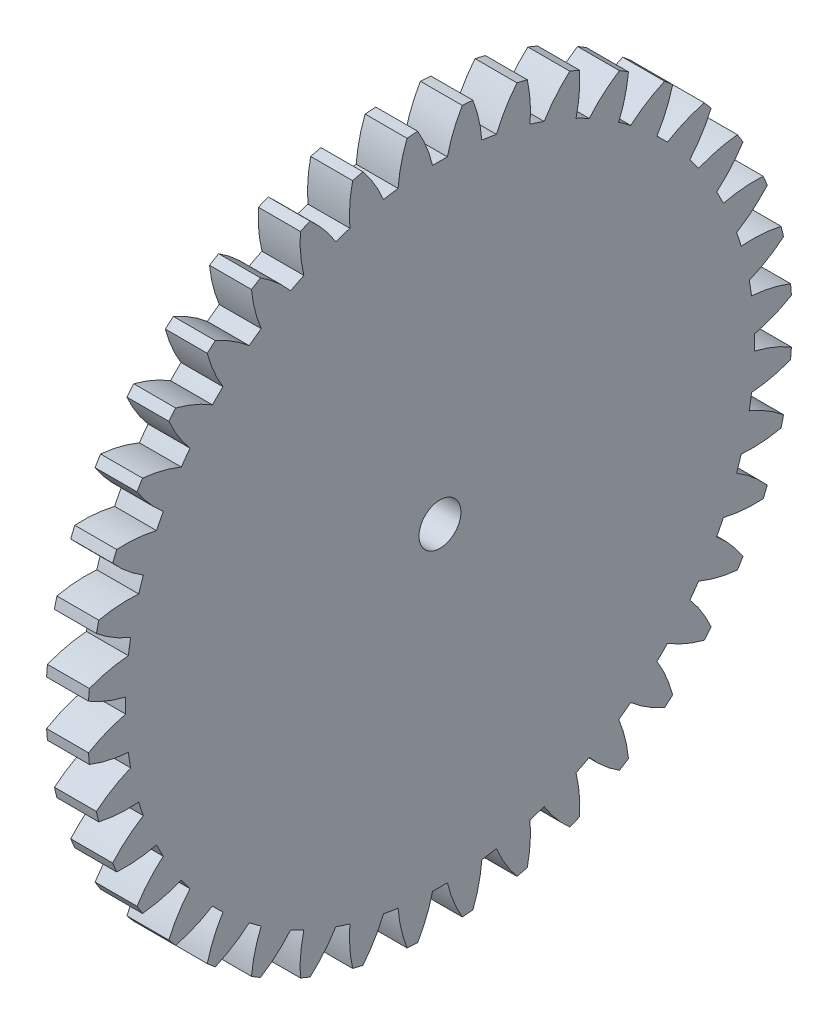
SolidWorks part; units mm, degrees
ref_plane "Plane1" through (0, 0, 0) normal (0, 0, 1) x (1, 0, 0)
ref_plane "Plane2" through (0, 0, 0) normal (0, 1, 0) x (1, 0, 0)
ref_plane "Plane3" through (0, 0, 0) normal (1, 0, 0) x (0, 0, -1)
sketch "HoldingSke" plane through (0, 0, 0) normal (0, 1, 0) x (1, 0, 0)
  line L0 (0, 0) -> (0.383, -0.3214)
  line L1 (-15, 0) -> (100, 0) construction
  line L2 (0, 0) -> (-2.1039, 2.3779)
  line L3 (0, 0) -> (-11.863, 4.5341)
  line L4 (0, 0) -> (6.6156, 5.5511)
  line L5 (0, 0) -> (-46.8476, -17.4728)
  line L6 (0, 0) -> (-4.1448, -2.7965)
  line L7 (-2.1039, 2.3779) -> (8.6586, 51.2059)
  line L8 (-76.2, 54.61) -> (-75.3, 54.61)
  line L9 (-71.009, 38.7566) -> (-53.1078, 45.2721)
  line L10 (-76.2, 71.12) -> (104.1128, 71.12)
  line L11 (0, 0) -> (-5, 0)
  line L12 (-76.2, 101.6) -> (-76.133, 101.6)
  line L13 (24.9733, 27.94) -> (52.9518, 28.4284)
  line L14 (24.9733, 27.94) -> (24.9743, 27.94)
  line L15 (24.9733, 27.94) -> (100.4006, 29.5858)
  line L16 (-63.627, -2) -> (-12.827, -2)
  circle A0 centre (0, 0) radius 2.5
  circle A1 centre (0, 0) radius 37.499
  circle A2 centre (0, 0) radius 37.5
  circle A3 centre (0, 0) radius 2.5
  dimension "MHD" = 74.998
  dimension "Hub_dia" = 75
  dimension "Bore" = 5
  dimension "MBD" = 5
  dimension "Num_teeth" = 40
  dimension "Pitch" = 0.5
  dimension "Overall_len" = 50
  dimension "Show_teeth" = 40
  dimension "Thickness" = 5
  dimension "OAL" = 50.0001
  dimension "T_dim" = 0.9
  dimension "Ap" = 20
  dimension "H" = 19.05
  dimension "Pitch_radius" = 180.3128
  dimension "Width" = 5
  dimension "Backlash" = 0.067
  dimension "Addendum_fac" = 1
  dimension "Dedendum_fac" = 1.25
  dimension "Clearance_fac" = 0.25
  dimension "Dedendum_add" = 0.001
  dimension "Module" = 2
sketch "BasProSke" plane through (0, 0, 0) normal (0, 1, 0) x (1, 0, 0)
  line L0 (-10, 0) -> (60, 0) construction
  line L1 (0, 0) -> (0, 42)
  line L2 (0, 0) -> (5, 0)
  line L3 (5, 0) -> (5, 42)
  line L4 (5, 42) -> (0, 42)
  dimension "Thickness" = 5
  dimension "Diameter" = 84
revolve "Base-Revolve" add sketch "BasProSke" angle 360 about L0
sketch "TooCutSke" plane through (0, 0, 0) normal (1, 0, 0) x (0, 0, -1)
  line L1 (0, 0) -> (0, 107) construction
  line L2 (0, 0) -> (-1.6876, 39.9644) construction
  line L3 (0, 0) -> (-6.2726, 79.7007) construction
  line L4 (-1.6876, 39.9644) -> (-3.1363, 39.8504) construction
  arc A0 (0.8828, 37.4886) -> (-0.8828, 37.4886) centre (0, 0) ccw
  arc A1 (2.6784, 41.94) -> (-2.6784, 41.94) centre (0, 0) ccw
  circle A2 centre (0, 0) radius 40 construction
  circle A3 centre (0, 0) radius 37.5877 construction
  arc A4 (-0.8828, 37.4886) -> (-2.6784, 41.94) centre (-16.451, 33.7965) ccw
  arc A5 (2.6784, 41.94) -> (0.8828, 37.4886) centre (16.451, 33.7965) ccw
  dimension "Root_dia" = 74.998
  dimension "Overcut_dia" = 84.0508
  dimension "Pitch_dia" = 80
  dimension "Base_dia" = 75.1754
  dimension "Flank_rad" = 16
  dimension "Half_ang" = 4.5
  dimension "Half_CT" = 1.4531
extrude "ToothCut" cut sketch "TooCutSke" along normal through all
fillet "Breaks" [suppressed] radius 0.04
fillet "RootFillets" [suppressed] radius 0.501
pattern_circular "TeethCuts" count 40 every 9 about axis through (-10, 0, 0) along (1, 0, 0) of "ToothCut", "RootFillets", "Breaks"
sketch "HubNeaOneSke" plane through (0, 0, 0) normal (-1, 0, 0) x (0, 0, 1)
  circle A0 centre (0, 0) radius 37.499
  dimension "Diameter" = 74.998
extrude "HubNearOne" [suppressed] add sketch "HubNeaOneSke" along normal blind 45.0001
sketch "HubNeaBotSke" plane through (0, 0, 0) normal (-1, 0, 0) x (0, 0, 1)
  circle A0 centre (0, 0) radius 37.499
  dimension "Diameter" = 74.998
extrude "HubNearBoth" [suppressed] add sketch "HubNeaBotSke" along normal blind 22.5
ref_plane "FarPln" through (5, 0, 0) normal (1, 0, 0) x (0, 0, -1)
sketch "HubFarSke" plane through (5, 0, 0) normal (1, 0, 0) x (0, 0, -1)
  circle A0 centre (0, 0) radius 37.499
  dimension "Diameter" = 74.998
extrude "HubFar" [suppressed] add sketch "HubFarSke" along normal blind 22.5
sketch "BorSke" plane through (0, 0, 0) normal (1, 0, 0) x (0, 0, -1)
  circle A0 centre (0, 0) radius 2.5
  dimension "Diameter" = 5
extrude "Bore" cut sketch "BorSke" along normal mid plane 100.0001
sketch "KeySke" plane through (0, 0, 0) normal (1, 0, 0) x (0, 0, -1)
  line L0 (-1, 0) -> (-1, 3.4)
  line L1 (-1, 3.4) -> (1, 3.4)
  line L2 (1, 3.4) -> (1, 0)
  line L3 (0, 0) -> (0, 34) construction
  line L4 (-1, 0) -> (1, 0)
  dimension "Offset" = 3.4
  dimension "Width" = 2
extrude "Keyway" [suppressed] cut sketch "KeySke" along normal mid plane 100.0001
pattern_circular "Keyway2" [suppressed] count 2 every 90 about axis through (-10, 0, 0) along (1, 0, 0)
equation "' \"Module@HoldingSke\" = 6.35"
equation "' \"Num_teeth@HoldingSke\" = 12"
equation "' \"Ap@HoldingSke\" =  20"
equation "' \"Ap@HoldingSke\" = 20"
equation "' \"Width@HoldingSke\" = 0.5 * 25.4"
equation "' \"Hub_dia@HoldingSke\"= 1 * 25.4"
equation "' \"Hub_dia@HoldingSke\" = 1 * 25.4"
equation "' \"Overall_len@HoldingSke\" = 1.0 * 25.4"
equation "' \"Bore@HoldingSke\" = 0.75 * 25.4"
equation "' \"T_dim@HoldingSke\" = 0.1 * 25.4"
equation "' \"Width@KeySke\" = 0.25 * 25.4"
equation "' \"Show_teeth@HoldingSke\" = 13"
equation "' \"Backlash@HoldingSke\" = 0.009 * 25.4"
equation "' \"Addendum_fac@HoldingSke\" = 1.0"
equation "' \"Dedendum_fac@HoldingSke\" = 1.25"
equation "' \"Dedendum_add@HoldingSke\" = 0.00005 * 25.4"
equation "' \"Clearance_fac@HoldingSke\" = 0.25"
equation "\"Pitch@HoldingSke\" = 1 / \"Module@HoldingSke\""
equation "\"Overcut_dia@TooCutSke\" = (\"Num_teeth@HoldingSke\" + 2 * \"Addendum_fac@HoldingSke\") / \"Pitch@HoldingSke\" + 0.002 * 25.4"
equation "\"Pitch_dia@TooCutSke\" = \"Num_teeth@HoldingSke\" / \"Pitch@HoldingSke\""
equation "\"Base_dia@TooCutSke\" = \"Num_teeth@HoldingSke\" / \"Pitch@HoldingSke\" * cos((\"Ap@HoldingSke\"  * 3.14159265 / 180))"
equation "\"Root_dia@TooCutSke\" = (\"Num_teeth@HoldingSke\" + 2) / \"Pitch@HoldingSke\" - 2 * (\"Addendum_fac@HoldingSke\" + \"Dedendum_fac@HoldingSke\") / \"Pitch@HoldingSke\" - \"Dedendum_add@HoldingSke\" * 2"
equation "\"Half_ang@TooCutSke\" = 180 / \"Num_teeth@HoldingSke\""
equation "\"Half_CT@TooCutSke\" = \"Num_teeth@HoldingSke\" / \"Pitch@HoldingSke\" * sin((3.14159265 / 2 / \"Num_teeth@HoldingSke\")) / 2 - 7 * \"Backlash@HoldingSke\" / 4"
equation "\"Flank_rad@TooCutSke\" = \"Num_teeth@HoldingSke\" / \"Pitch@HoldingSke\" / 5"
equation "\"Radius@RootFillets\" = \"Clearance_fac@HoldingSke\" / \"Pitch@HoldingSke\" + \"Dedendum_add@HoldingSke\""
equation "\"Break_rad@Breaks\" = 0.02 / \"Pitch@HoldingSke\""
equation "\"Thickness@HoldingSke\" = \"Width@HoldingSke\""
equation "\"OAL@HoldingSke\" = \"Thickness@HoldingSke\""
equation "\"MHD@HoldingSke\" = (\"Num_teeth@HoldingSke\" + 2) / \"Pitch@HoldingSke\" - 2 * (\"Addendum_fac@HoldingSke\" + \"Dedendum_fac@HoldingSke\")  / \"Pitch@HoldingSke\" - \"Dedendum_add@HoldingSke\" * 2"
equation "\"MBD@HoldingSke\" = (\"Num_teeth@HoldingSke\" + 2) / \"Pitch@HoldingSke\" - 2 * (\"Addendum_fac@HoldingSke\" + \"Dedendum_fac@HoldingSke\")  / \"Pitch@HoldingSke\" - \"Dedendum_add@HoldingSke\" * 2 - 0.002 * 25.4"
equation "\"MHD@HoldingSke\" = ((sgn( \"MHD@HoldingSke\" - \"Hub_dia@HoldingSke\" )-1)*( \"MHD@HoldingSke\" - \"Hub_dia@HoldingSke\" ))/-2+ \"Hub_dia@HoldingSke\""
equation "\"MBD@HoldingSke\" = ((sgn( \"MBD@HoldingSke\" - \"Bore@HoldingSke\" )-1)*( \"MBD@HoldingSke\" - \"Bore@HoldingSke\" ))/-2+ \"Bore@HoldingSke\""
equation "\"OAL@HoldingSke\" = ((sgn( \"OAL@HoldingSke\" - \"Overall_len@HoldingSke\" )+1)*( \"OAL@HoldingSke\" - \"Overall_len@HoldingSke\" ))/2 + \"Overall_len@HoldingSke\" + 0.000002 * 25.4"
equation "\"Num_teeth@TeethCuts\" = int( \"Show_teeth@HoldingSke\" ) + 1"
equation "\"Num_teeth@TeethCuts\" = ((sgn( \"Num_teeth@TeethCuts\" - \"Num_teeth@HoldingSke\" )-1)*( \"Num_teeth@TeethCuts\" - \"Num_teeth@HoldingSke\" ))/-2+ \"Num_teeth@HoldingSke\""
equation "\"Num_teeth@TeethCuts\" = ((sgn( \"Num_teeth@TeethCuts\" - 2.0)+1)*( \"Num_teeth@TeethCuts\" - 2.0))/2 +2.0"
equation "\"Angle@TeethCuts\" = 360.0 / \"Num_teeth@HoldingSke\""
equation "\"Diameter@BasProSke\" = (\"Num_teeth@HoldingSke\" + 2 * \"Addendum_fac@HoldingSke\") / \"Pitch@HoldingSke\""
equation "\"Thickness@BasProSke\"  = \"Thickness@HoldingSke\""
equation "' \"Fillet_rad@BasProSke\" =  \"Thickness@HoldingSke\" * 0.05"
equation "' \"Fillet_rad@BasProSke\" = \"Thickness@HoldingSke\" * 0.05"
equation "\"MHD@HoldingSke\" = ((sgn( \"MHD@HoldingSke\" - \"Root_dia@TooCutSke\" )-1)*( \"MHD@HoldingSke\" - \"Root_dia@TooCutSke\" ))/-2+ \"Root_dia@TooCutSke\""
equation "\"Diameter@HubNeaOneSke\" = \"MHD@HoldingSke\""
equation "\"Length@HubNearOne\" = \"OAL@HoldingSke\" - \"Thickness@BasProSke\""
equation "\"Diameter@HubNeaBotSke\" = \"MHD@HoldingSke\""
equation "\"Length@HubNearBoth\" = ( \"OAL@HoldingSke\" - \"Thickness@BasProSke\" ) / 2.0"
equation "\"Thickness@FarPln\" = \"Thickness@BasProSke\""
equation "\"Diameter@HubFarSke\" = \"MHD@HoldingSke\""
equation "\"Length@HubFar\" = ( \"OAL@HoldingSke\" - \"Thickness@BasProSke\" ) / 2.0"
equation "\"Diameter@BorSke\" = \"MBD@HoldingSke\""
equation "\"D1@Bore\" = \"OAL@HoldingSke\" * 2.0"
equation "\"D1@Keyway\" = \"OAL@HoldingSke\" * 2.0"
equation "\"Offset@KeySke\" = \"T_dim@HoldingSke\" + \"MBD@HoldingSke\" / 2.0"
